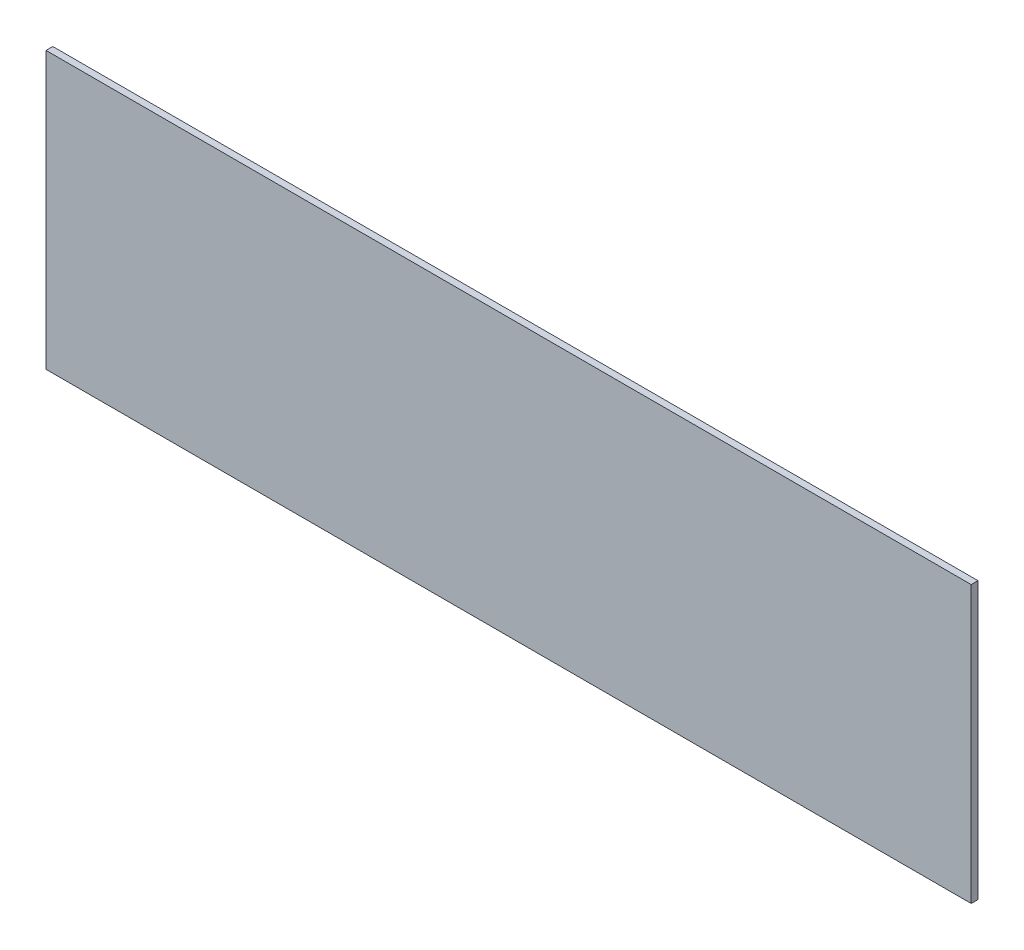
SolidWorks part; units mm, degrees
ref_plane "Plan de face" through (0, 0, 0) normal (0, 0, 1) x (1, 0, 0)
ref_plane "Plan de dessus" through (0, 0, 0) normal (0, 1, 0) x (1, 0, 0)
ref_plane "Plan de droite" through (0, 0, 0) normal (1, 0, 0) x (0, 0, -1)
sketch "Esquisse1" plane through (0, 0, 0) normal (0, 0, 1) x (1, 0, 0)
  line L1 (-273, -81.5) -> (273, -81.5)
  line L2 (-273, -81.5) -> (-273, 81.5)
  line L3 (-273, 81.5) -> (273, 81.5)
  line L4 (273, -81.5) -> (273, 81.5)
  line L5 (-273, -81.5) -> (273, 81.5) construction
  line L6 (-273, 81.5) -> (273, -81.5) construction
  point P0 (0, 0)
  dimension "D1" = 163
  dimension "D2" = 546
extrude "Boss.-Extru.1" add sketch "Esquisse1" along normal blind 4
